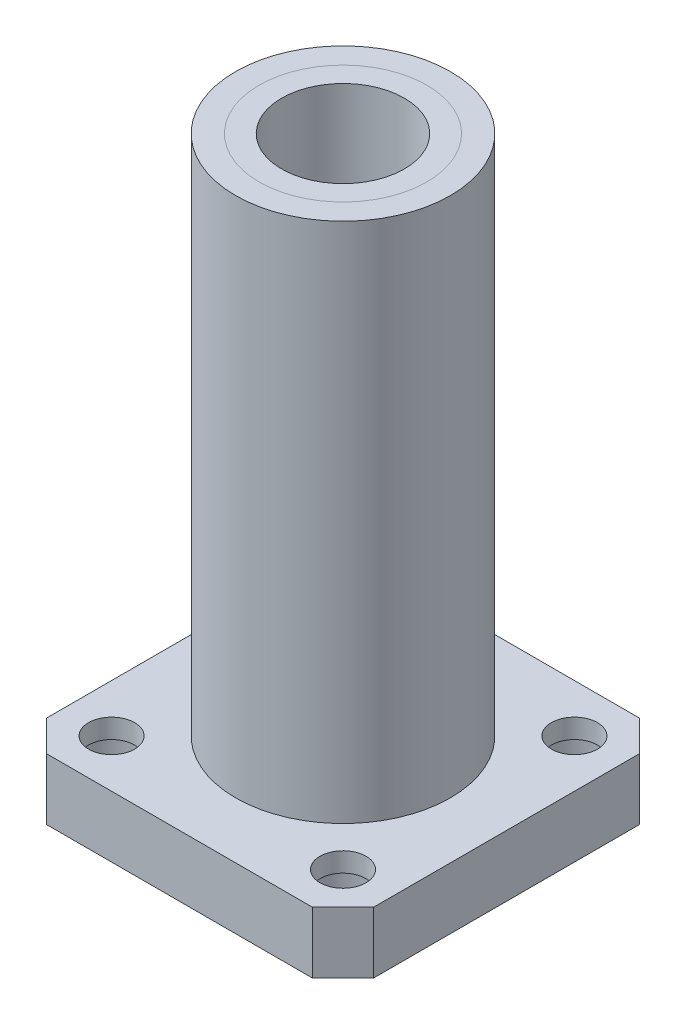
SolidWorks part; units mm, degrees
ref_plane "Front Plane" through (0, 0, 0) normal (0, 0, 1) x (1, 0, 0)
ref_plane "Top Plane" through (0, 0, 0) normal (0, 1, 0) x (1, 0, 0)
ref_plane "Right Plane" through (0, 0, 0) normal (1, 0, 0) x (0, 0, -1)
sketch "Sketch1" plane through (0, 0, 0) normal (0, 1, 0) x (1, 0, 0)
  circle A0 centre (0, 0) radius 10.5
  circle A1 centre (0, 0) radius 6
  dimension "D1" = 21
  dimension "D2" = 12
extrude "Boss-Extrude1" add sketch "Sketch1" along normal blind 57
sketch "Sketch2" plane through (0, 0, 0) normal (0, 1, 0) x (1, 0, 0)
  line L1 (-16, 16) -> (16, 16)
  line L2 (-16, 16) -> (-16, -16)
  line L3 (-16, -16) -> (16, -16)
  line L4 (16, 16) -> (16, -16)
  line L5 (-16, 16) -> (16, -16) construction
  line L6 (-16, -16) -> (16, 16) construction
  circle A0 centre (0, 0) radius 14.1471 construction
  circle A1 centre (0, 0) radius 6
  point P0 (0, 0)
  dimension "D3" = 12
  dimension "D1" = 32
  dimension "D2" = 32
extrude "Boss-Extrude2" add sketch "Sketch2" along normal blind 6
sketch "Sketch3" plane through (0, 0, 0) normal (0, 1, 0) x (1, 0, 0)
  line L1 (-11.3137, 11.3137) -> (11.3137, 11.3137) construction
  line L2 (-11.3137, 11.3137) -> (-11.3137, -11.3137) construction
  line L3 (-11.3137, -11.3137) -> (11.3137, -11.3137) construction
  line L4 (11.3137, 11.3137) -> (11.3137, -11.3137) construction
  line L5 (-11.3137, 11.3137) -> (11.3137, -11.3137) construction
  line L6 (-11.3137, -11.3137) -> (11.3137, 11.3137) construction
  circle A0 centre (-11.3137, 11.3137) radius 2.25
  circle A1 centre (-11.3137, -11.3137) radius 2.25
  circle A2 centre (11.3137, -11.3137) radius 2.25
  circle A3 centre (11.3137, 11.3137) radius 2.25
  circle A4 centre (0, 0) radius 16 construction
  point P0 (0, 0)
  dimension "D2" = 32
  dimension "D1" = 4.5
extrude "Cut-Extrude1" cut sketch "Sketch3" along normal through all
chamfer "Chamfer1" distance 3 angle 45 4 edges at (16, 3, -16) (16, 3, 16) (-16, 3, 16) (-16, 3, -16)
sketch "Sketch4" plane through (0, 0, 0) normal (0, 1, 0) x (1, 0, 0)
  circle A0 centre (0, 0) radius 8.2
  circle A1 centre (0, 0) radius 6 construction
  dimension "D1" = 2.2
split line "Split Line1"
sketch "Sketch5" plane through (0, 0, 0) normal (0, -1, 0) x (1, 0, 0)
  circle A0 centre (-11.3137, 11.3137) radius 3.75
  circle A1 centre (11.3137, 11.3137) radius 3.75
  circle A2 centre (11.3137, -11.3137) radius 3.75
  circle A3 centre (-11.3137, -11.3137) radius 3.75
  dimension "D1" = 7.5
extrude "Cut-Extrude2" cut sketch "Sketch5" against normal blind 4.1
equation "\"dmin\"= 12"
equation "\"dmax\"= 21"
equation "\"l\"= 57"
equation "\"k\"= 32"
equation "\"b\"= 6"
equation "\"holespace\"= 32"
equation "\"holes\"= 4.5"
equation "\"D1@Boss-Extrude1\"=\"l\""
equation "\"D2@Sketch1\"=\"dmin\""
equation "\"D1@Sketch1\"=\"dmax\""
equation "\"D3@Sketch2\"=\"dmin\""
equation "\"D1@Sketch2\"=\"k\""
equation "\"D2@Sketch2\"=\"k\""
equation "\"D1@Boss-Extrude2\"=\"b\""
equation "\"D2@Sketch3\"=\"holespace\""
equation "\"D1@Sketch3\"=\"holes\""
equation "\"chamfer\"= 3"
equation "\"D1@Chamfer1\"=\"chamfer\""
equation "\"screw_head_d\"= 7.5"
equation "\"screw_head_h\"= 4.1"
equation "\"D1@Sketch5\"=\"screw_head_d\""
equation "\"D1@Cut-Extrude2\"=\"screw_head_h\""
